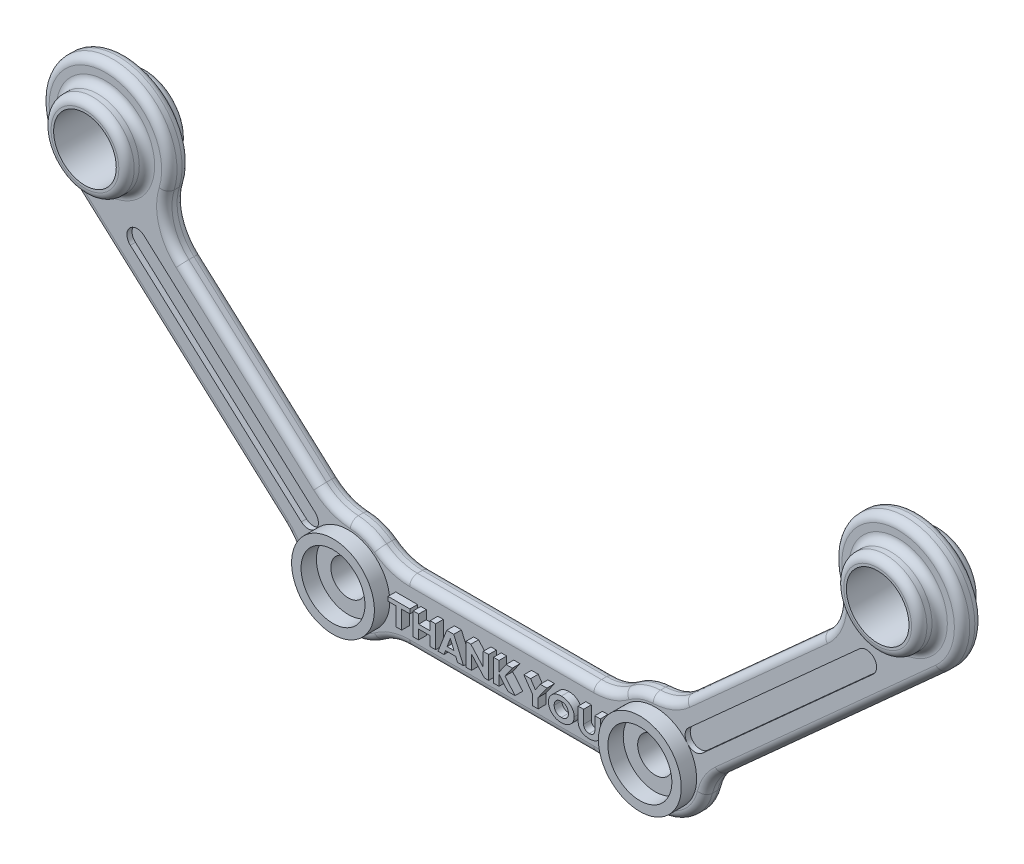
SolidWorks part; units mm, degrees
ref_plane "Front Plane" through (0, 0, 0) normal (0, 0, 1) x (1, 0, 0)
ref_plane "Top Plane" through (0, 0, 0) normal (0, 1, 0) x (1, 0, 0)
ref_plane "Right Plane" through (0, 0, 0) normal (1, 0, 0) x (0, 0, -1)
sketch "Sketch1" plane through (0, 0, 0) normal (0, 0, 1) x (1, 0, 0)
  line L0 (0, 0) -> (0, -56.8) construction
  line L1 (-77.5, 0) -> (0, 0) construction
  line L2 (-33.0982, -56.8) -> (-0.2147, -56.8) construction
  line L3 (-28.4918, -44.8) -> (-0.2147, -44.8) construction
  line L4 (85.8641, -9.2893) -> (39.9977, -50.5876)
  line L5 (-68.5527, -8.729) -> (-32.5632, -41.1341)
  line L6 (-22, -44.8) -> (22, -44.8)
  line L7 (-85.8641, -9.2893) -> (-39.9977, -50.5876)
  line L8 (-22, -56.8) -> (22, -56.8)
  line L9 (-74.5417, -3.3365) -> (-28.4918, -44.8) construction
  line L10 (-82.5713, -12.2542) -> (-33.0982, -56.8) construction
  line L11 (68.5527, -8.729) -> (32.5632, -41.1341)
  line L12 (30, -50.8) -> (0, -50.8) construction
  line L13 (14.3611, -50.8) -> (14.3611, -44.8) construction
  line L14 (14.3611, -50.8) -> (14.3611, -56.8) construction
  circle A0 centre (-77.5, 0) radius 6.25
  arc A1 (-68.5527, -8.729) -> (-85.8641, -9.2893) centre (-77.5, 0) ccw
  arc A2 (68.5527, -8.729) -> (85.8641, -9.2893) centre (77.5, 0) cw
  circle A3 centre (77.5, 0) radius 6.25
  circle A4 centre (30, -50.8) radius 3.429
  arc A5 (32.5632, -41.1341) -> (22, -44.8) centre (30, -50.8) ccw
  arc A6 (22, -56.8) -> (39.9977, -50.5876) centre (30, -50.8) ccw
  arc A7 (-22, -56.8) -> (-39.9977, -50.5876) centre (-30, -50.8) cw
  circle A8 centre (-30, -50.8) radius 3.429
  arc A9 (-32.5632, -41.1341) -> (-22, -44.8) centre (-30, -50.8) cw
  point P15 (0, -44.8)
  dimension "D1" = 12.5
  dimension "D2" = 25
  dimension "D7" = 6.858
  dimension "D8" = 20
  dimension "D3" = 56.8
  dimension "D4" = 138
  dimension "D6" = 30
  dimension "D5" = 12
extrude "Boss-Extrude1" add sketch "Sketch1" along normal mid plane 4
sketch "Sketch7" plane through (0, 0, 2) normal (0, 0, 1) x (1, 0, 0)
  line L0 (0, 0) -> (0, -26.7661) construction
  circle A0 centre (-77.5, 0) radius 6.125
  circle A1 centre (-77.5, 0) radius 8.125
  circle A2 centre (77.5, 0) radius 8.125
  circle A3 centre (77.5, 0) radius 6.125
  dimension "D1" = 12.25
  dimension "D2" = 16.25
extrude "Boss-Extrude5" add sketch "Sketch7" along normal blind 4 and the other way blind 8
sketch "Sketch3" plane through (0, 0, 2) normal (0, 0, 1) x (1, 0, 0)
  text T0 "THANK YOU" font "Gill Sans MT" height in points 18
extrude "Thank You" add sketch "Sketch3" along normal blind 1.5
sketch "Sketch12" plane through (0, 0, -2) normal (0, 0, -1) x (-1, 0, 0)
  text T0 "COPTER" font "Gill Sans MT" height in points 24
extrude "Boss-Extrude7" add sketch "Sketch12" along normal blind 1.5
sketch "Sketch14" plane through (0, 0, 2) normal (0, 0, 1) x (1, 0, 0)
  line L0 (-71.2935, -14.335) -> (-37.852, -44.4459) construction
  line L1 (-69.9552, -12.8487) -> (-36.5137, -42.9596)
  line L2 (-72.6318, -15.8213) -> (-39.1902, -45.9321)
  line L3 (-54.5727, -29.3904) -> (-50.558, -24.9315) construction
  line L4 (-68.5527, -8.729) -> (-32.5632, -41.1341) construction
  line L5 (-54.5727, -29.3904) -> (-58.5875, -33.8493) construction
  line L7 (-85.8641, -9.2893) -> (-39.9977, -50.5876) construction
  line L8 (0, 0) -> (0, -20.7501) construction
  line L9 (71.2935, -14.335) -> (37.852, -44.4459) construction
  line L10 (69.9552, -12.8487) -> (36.5137, -42.9596)
  line L11 (72.6318, -15.8213) -> (39.1902, -45.9321)
  line L12 (54.5727, -29.3904) -> (58.5875, -33.8493) construction
  line L13 (54.5727, -29.3904) -> (50.558, -24.9315) construction
  line L14 (-68.5527, -8.729) -> (-71.2935, -14.335) construction
  line L15 (-32.5632, -41.1341) -> (-37.852, -44.4459) construction
  arc A0 (-69.9552, -12.8487) -> (-72.6318, -15.8213) centre (-71.2935, -14.335) ccw
  arc A1 (-39.1902, -45.9321) -> (-36.5137, -42.9596) centre (-37.852, -44.4459) ccw
  arc A3 (69.9552, -12.8487) -> (72.6318, -15.8213) centre (71.2935, -14.335) cw
  arc A4 (39.1902, -45.9321) -> (36.5137, -42.9596) centre (37.852, -44.4459) cw
  point P2 (-54.5727, -29.3904)
  point P21 (54.5727, -29.3904)
  dimension "D1" = 4
  dimension "D2" = 45
extrude "Cut-Extrude3" cut sketch "Sketch14" against normal blind 1
mirror "Mirror1" about plane through (0, 0, 0) normal (0, 0, 1) of "Cut-Extrude3"
fillet "Fillet1" radius 10 10 edges at (-39.9977, -50.5876, 0) (-22, -56.8, 0) (22, -56.8, 0) (39.9977, -50.5876, 0) (22, -44.8, 0) (32.5632, -41.1341, 0) (68.5527, -8.729, 0) (-22, -44.8, 0) (-32.5632, -41.1341, 0) (-68.5527, -8.729, 0)
fillet "Fillet2" radius 1.5 52 edges at (-65.6229, -9.258, -2) (-49.2201, -26.1361, -2) (-32.8711, -40.0717, -2) (-26.6183, -41.3891, -2) (-21.1623, -44.2868, -2) (0, -44.8, -2) (21.1623, -44.2868, -2) (26.6183, -41.3891, -2) (32.8711, -40.0717, -2) (49.2201, -26.1361, -2) (65.6229, -9.258, -2) (80.8378, 12.0461, -2) (64.2998, -28.7059, -2) (40.8439, -50.4223, -2) (33.3693, -60.2153, -2) (21.1623, -57.3132, -2) (0, -56.8, -2) (-21.1623, -57.3132, -2) (-33.3693, -60.2153, -2) (-40.8439, -50.4223, -2) (-64.2998, -28.7059, -2) (-65.6229, -9.258, 2) (-49.2201, -26.1361, 2) (-32.8711, -40.0717, 2) (-26.6183, -41.3891, 2) (-21.1623, -44.2868, 2) (0, -44.8, 2) (21.1623, -44.2868, 2) (26.6183, -41.3891, 2) (32.8711, -40.0717, 2) (49.2201, -26.1361, 2) (65.6229, -9.258, 2) (80.8378, 12.0461, 2) (64.2998, -28.7059, 2) (40.8439, -50.4223, 2) (33.3693, -60.2153, 2) (21.1623, -57.3132, 2) (0, -56.8, 2) (-21.1623, -57.3132, 2) (-33.3693, -60.2153, 2) (-40.8439, -50.4223, 2) (-64.2998, -28.7059, 2) (-80.8378, 12.0461, -2) (-80.8378, 12.0461, 2) (85.625, 0, 2) (69.375, 0, 6) (85.625, 0, -2) (69.375, 0, -6) (-69.375, 0, -2) (-69.375, 0, -6) (-69.375, 0, 6) (-69.375, 0, 2)
sketch "Sketch15" plane through (0, 0, 2) normal (0, 0, 1) x (1, 0, 0)
  line L0 (0, 0) -> (0, -25.3665) construction
  circle A0 centre (-30, -50.8) radius 6.25
  circle A1 centre (-30, -50.8) radius 8.1
  circle A2 centre (30, -50.8) radius 8.1
  circle A3 centre (30, -50.8) radius 6.25
  dimension "D1" = 12.5
  dimension "D2" = 16.2
extrude "Boss-Extrude8" add sketch "Sketch15" along normal blind 3
